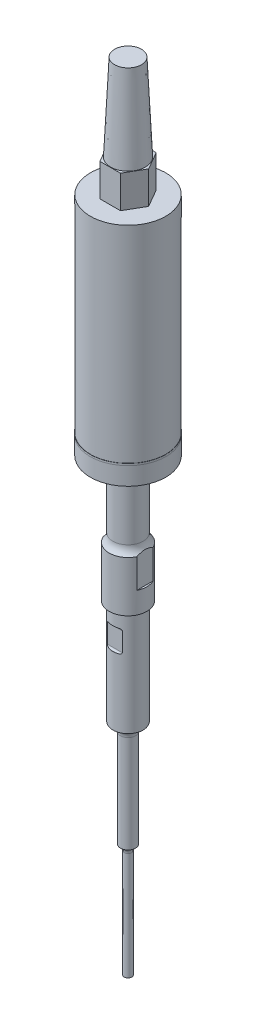
SolidWorks part; units mm, degrees
ref_plane "Front Plane" through (0, 0, 0) normal (0, 0, 1) x (1, 0, 0)
ref_plane "Top Plane" through (0, 0, 0) normal (0, 1, 0) x (1, 0, 0)
ref_plane "Right Plane" through (0, 0, 0) normal (1, 0, 0) x (0, 0, -1)
sketch "Sketch1" plane through (0, 0, 0) normal (0, 0, 1) x (1, 0, 0)
  line L0 (0, 0) -> (15.875, 0)
  line L1 (15.875, 0) -> (15.875, -95.25)
  line L2 (15.875, -95.25) -> (7.75, -95.25)
  line L3 (6.35, -99.25) -> (6.35, -123.35)
  line L5 (7.9375, -126.85) -> (7.9375, -148.15)
  line L6 (7.9375, -148.15) -> (6.35, -148.15)
  line L7 (6.35, -148.15) -> (6.35, -192.25)
  line L9 (3.15, -195.95) -> (3.15, -236.95)
  line L11 (1.6, -239.35) -> (1.6, -284.75)
  line L12 (1.6, -284.75) -> (0, -284.75)
  line L13 (0, -284.75) -> (0, 0)
  line L14 (-1.6, -239.35) -> (-1.6, -284.75) construction
  line L16 (-3.15, -195.95) -> (-3.15, -236.95) construction
  line L18 (-6.35, -148.15) -> (-6.35, -192.25) construction
  line L19 (-7.9375, -148.15) -> (-6.35, -148.15) construction
  line L20 (-7.9375, -126.85) -> (-7.9375, -148.15) construction
  line L22 (-6.35, -99.25) -> (-6.35, -123.35) construction
  line L23 (-15.875, -95.25) -> (-7.75, -95.25) construction
  line L24 (-15.875, 0) -> (-15.875, -95.25) construction
  arc A0 (6.35, -99.25) -> (7.75, -95.25) centre (12.7643, -99.25) cw
  arc A1 (-6.35, -99.25) -> (-7.75, -95.25) centre (-12.7643, -99.25) ccw construction
  arc A2 (6.35, -123.35) -> (7.9375, -126.85) centre (11.002, -123.35) ccw
  arc A3 (-6.35, -123.35) -> (-7.9375, -126.85) centre (-11.002, -123.35) cw construction
  arc A4 (1.6, -239.35) -> (3.15, -236.95) centre (4.2331, -239.35) cw
  arc A5 (-1.6, -239.35) -> (-3.15, -236.95) centre (-4.2331, -239.35) ccw construction
  arc A6 (3.15, -195.95) -> (6.35, -192.25) centre (6.8891, -195.95) cw
  arc A7 (-3.15, -195.95) -> (-6.35, -192.25) centre (-6.8891, -195.95) ccw construction
  point P34 (0, 0)
  dimension "D1" = 31.75
  dimension "D2" = 95.25
  dimension "D3" = 12.7
  dimension "D4" = 21.3
  dimension "D5" = 31.6
  dimension "D6" = 44.1
  dimension "D7" = 44.7
  dimension "D8" = 47.8
  dimension "D9" = 3.2
  dimension "D10" = 6.3
  dimension "D11" = 12.7
  dimension "D12" = 15.875
  dimension "D13" = 4
  dimension "D14" = 15.5
  dimension "D15" = 3.5
  dimension "D16" = 2.4
  dimension "D17" = 3.7
revolve "Revolve1" add sketch "Sketch1" angle 360 about L13
sketch "Sketch3" plane through (0, 0, 0) normal (0, 0, 1) x (1, 0, 0)
  line L0 (-7.9375, -126.85) -> (-7.9375, -148.15)
  line L1 (7.9375, -148.15) -> (7.9375, -126.85)
  line L2 (7.9375, -139.15) -> (7.9375, -126.85)
  line L3 (0, -17.4625) -> (0, 17.4625) construction
  line L4 (7.9375, -139.15) -> (7.1438, -139.15)
  line L5 (7.1438, -139.15) -> (7.1437, -125.949)
  line L6 (-7.1438, -139.15) -> (-7.1437, -125.949)
  line L7 (-7.9375, -139.15) -> (-7.1438, -139.15)
  line L8 (-7.9375, -139.15) -> (-7.9375, -126.85)
  arc A0 (-7.9375, -126.85) -> (-6.35, -123.35) centre (-11.002, -123.35) ccw
  arc A1 (6.35, -123.35) -> (7.9375, -126.85) centre (11.002, -123.35) ccw
  arc A2 (7.1437, -125.949) -> (7.9375, -126.85) centre (11.002, -123.35) ccw
  arc A4 (-7.1437, -125.949) -> (-7.9375, -126.85) centre (-11.002, -123.35) cw
  dimension "D1" = 9
  dimension "D2" = 14.2875
extrude "Cut-Extrude1" cut sketch "Sketch3" against normal through all both and the other way through all
sketch "Sketch4" plane through (0, 0, 0) normal (1, 0, 0) x (0, 0, -1)
  line L0 (-6.35, -148.15) -> (-6.35, -192.25)
  line L1 (6.35, -192.25) -> (6.35, -148.15)
  line L2 (6.35, -192.25) -> (6.35, -148.15) construction
  line L3 (0, 17.4625) -> (0, -17.4625) construction
  line L4 (6.35, -163.5805) -> (6.2245, -163.5805)
  line L5 (6.35, -163.5805) -> (6.35, -154.1825)
  line L6 (6.35, -154.1825) -> (6.2245, -154.1825)
  line L7 (5.5245, -162.8805) -> (5.5245, -154.8825)
  line L8 (-5.5245, -162.8805) -> (-5.5245, -154.8825)
  line L9 (-6.35, -154.1825) -> (-6.2245, -154.1825)
  line L10 (-6.35, -163.5805) -> (-6.35, -154.1825)
  line L11 (-6.35, -163.5805) -> (-6.2245, -163.5805)
  arc A0 (6.2245, -163.5805) -> (5.5245, -162.8805) centre (6.2245, -162.8805) cw
  arc A1 (5.5245, -154.8825) -> (6.2245, -154.1825) centre (6.2245, -154.8825) cw
  arc A2 (-5.5245, -154.8825) -> (-6.2245, -154.1825) centre (-6.2245, -154.8825) ccw
  arc A3 (-6.2245, -163.5805) -> (-5.5245, -162.8805) centre (-6.2245, -162.8805) ccw
  point P22 (-5.5245, -158.8815)
  dimension "D1" = 0.7
  dimension "D2" = 9.398
  dimension "D3" = 11.049
  dimension "D4" = 6.0325
extrude "Cut-Extrude2" cut sketch "Sketch4" against normal through all both and the other way through all
sketch "Sketch5" plane through (0, 0, 0) normal (0, 1, 0) x (1, 0, 0)
  line L1 (-4.3371, 7.5121) -> (-8.6742, 0)
  line L2 (-8.6742, 0) -> (-4.3371, -7.512)
  line L3 (-4.3371, -7.512) -> (4.3371, -7.512)
  line L4 (4.3371, -7.512) -> (8.6742, 0)
  line L5 (8.6742, 0) -> (4.3371, 7.512)
  line L6 (4.3371, 7.512) -> (-4.3371, 7.5121)
  circle A0 centre (0, 0) radius 7.512 construction
  dimension "D1" = 15.0241
extrude "Boss-Extrude1" add sketch "Sketch5" along normal blind 13.7
sketch "Sketch6" plane through (0, 0, 0) normal (0, 0, 1) x (1, 0, 0)
  line L0 (8.6742, 13.7) -> (-8.6742, 13.7)
  line L1 (7.35, 13.7) -> (0, 13.7)
  line L2 (0, 13.7) -> (0, 50.2)
  line L3 (0, 50.2) -> (5.65, 50.2)
  line L4 (5.65, 50.2) -> (7.35, 13.7)
  dimension "D1" = 5.65
  dimension "D2" = 7.35
  dimension "D3" = 36.5
revolve "Revolve2" add sketch "Sketch6" angle 360 about L2
sketch "Sketch7" plane through (0, 0, 0) normal (0, 0, 1) x (1, 0, 0)
  line L0 (15.875, -95.25) -> (15.875, 0) construction
  line L1 (15.875, -87.65) -> (15.975, -87.65)
  line L2 (15.875, -87.65) -> (15.875, -86.85)
  line L3 (15.875, -86.85) -> (15.975, -86.85)
  line L4 (15.975, -87.65) -> (15.975, -86.85)
  dimension "D1" = 7.6
  dimension "D2" = 0.8
  dimension "D3" = 0.1
revolve "Revolve3" add sketch "Sketch7" angle 360 about L13
